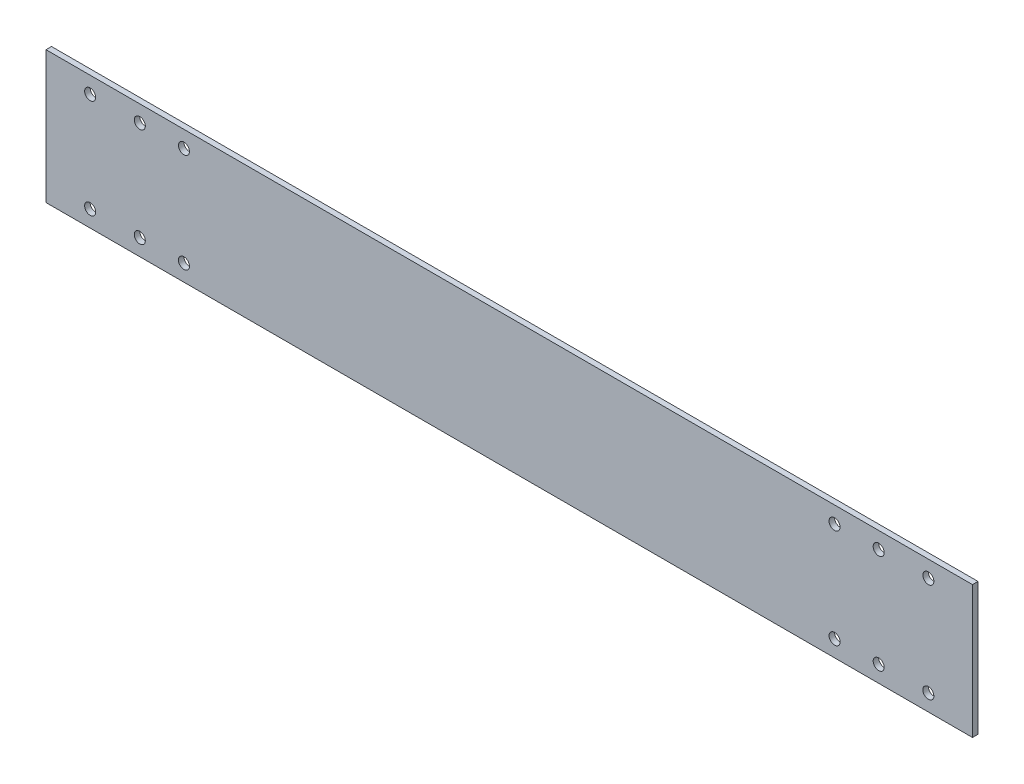
SolidWorks part; units mm, degrees
material "6061-T6 (SS)"
ref_plane "Front Plane" through (0, 0, 0) normal (0, 0, 1) x (1, 0, 0)
ref_plane "Top Plane" through (0, 0, 0) normal (0, 1, 0) x (1, 0, 0)
ref_plane "Right Plane" through (0, 0, 0) normal (1, 0, 0) x (0, 0, -1)
sketch "Sketch1" plane through (0, -330.2, 0) normal (0, 0, 1) x (1, 0, 0)
  line L1 (-247.2046, 6612.1072) -> (285.9414, 6612.1072)
  line L2 (-247.2046, 6612.1072) -> (-247.2046, 6535.9072)
  line L3 (-247.2046, 6535.9072) -> (285.9414, 6535.9072)
  line L4 (285.9414, 6612.1072) -> (285.9414, 6535.9072)
  dimension "D1" = 76.2
  dimension "D2" = 533.146
extrude "Boss-Extrude1" add sketch "Sketch1" along normal blind 3.175
sketch "Sketch2" plane through (0, 0, 0) normal (0, 0, -1) x (-1, 0, 0)
  line L0 (-285.9414, 6281.9072) -> (247.2046, 6281.9072) construction
  line L1 (215.4546, 6281.9072) -> (171.0046, 6281.9072)
  line L2 (215.4546, 6281.9072) -> (215.4546, 6205.7072)
  line L3 (215.4546, 6205.7072) -> (171.0046, 6205.7072)
  line L4 (171.0046, 6281.9072) -> (171.0046, 6205.7072)
  line L5 (247.2046, 6205.7072) -> (-285.9414, 6205.7072) construction
  line L6 (247.2046, 6281.9072) -> (247.2046, 6205.7072) construction
  line L7 (-19.3684, 6281.9072) -> (-19.3684, 6205.7072) construction
  line L8 (-209.7414, 6281.9072) -> (-209.7414, 6205.7072)
  line L9 (-254.1914, 6205.7072) -> (-209.7414, 6205.7072)
  line L10 (-254.1914, 6281.9072) -> (-254.1914, 6205.7072)
  line L11 (-254.1914, 6281.9072) -> (-209.7414, 6281.9072)
  dimension "D1" = 44.45
  dimension "D2" = 31.75
split line "Split Line1" [suppressed]
hole_wizard "1/4 (0.25) Diameter Hole1" positions "Sketch6" profile "Sketch7" hole size "1/4" standard "ANSI Inch" end condition through all
sketch "Sketch6" plane through (0, 0, 0) normal (0, 0, -1) x (-1, 0, 0)
  line L0 (-19.3684, 6281.9072) -> (-19.3684, 6205.7072) construction
  line L1 (-285.9414, 6281.9072) -> (247.2046, 6281.9072) construction
  line L2 (247.2046, 6205.7072) -> (-285.9414, 6205.7072) construction
  line L3 (-285.9414, 6205.7072) -> (-285.9414, 6281.9072) construction
  point P0 (-231.9664, 6215.2322)
  point P3 (-206.5664, 6215.2322)
  point P6 (-206.5664, 6272.3822)
  point P9 (-231.9664, 6272.3822)
  point P27 (-260.5414, 6215.2322)
  point P29 (-260.5414, 6272.3822)
  point P37 (221.8046, 6272.3822)
  point P38 (221.8046, 6215.2322)
  point P39 (193.2296, 6272.3822)
  point P40 (167.8296, 6272.3822)
  point P41 (167.8296, 6215.2322)
  point P42 (193.2296, 6215.2322)
  dimension "D1" = 25.4
sketch "Sketch7" plane through (231.9664, 6215.2322, 0) normal (1, 0, 0) x (0, 1, 0)
  line L0 (0, 0) -> (0, 3.175)
  line L1 (0, 3.175) -> (3.175, 3.175)
  line L2 (3.175, 3.175) -> (3.175, 0)
  line L5 (3.175, 0) -> (0, 0)
  line L11 (0, -6.35) -> (0, 107.95) construction
  dimension "Thru Hole Dia." = 6.35
  dimension "Thru Hole Depth" = 3.175
